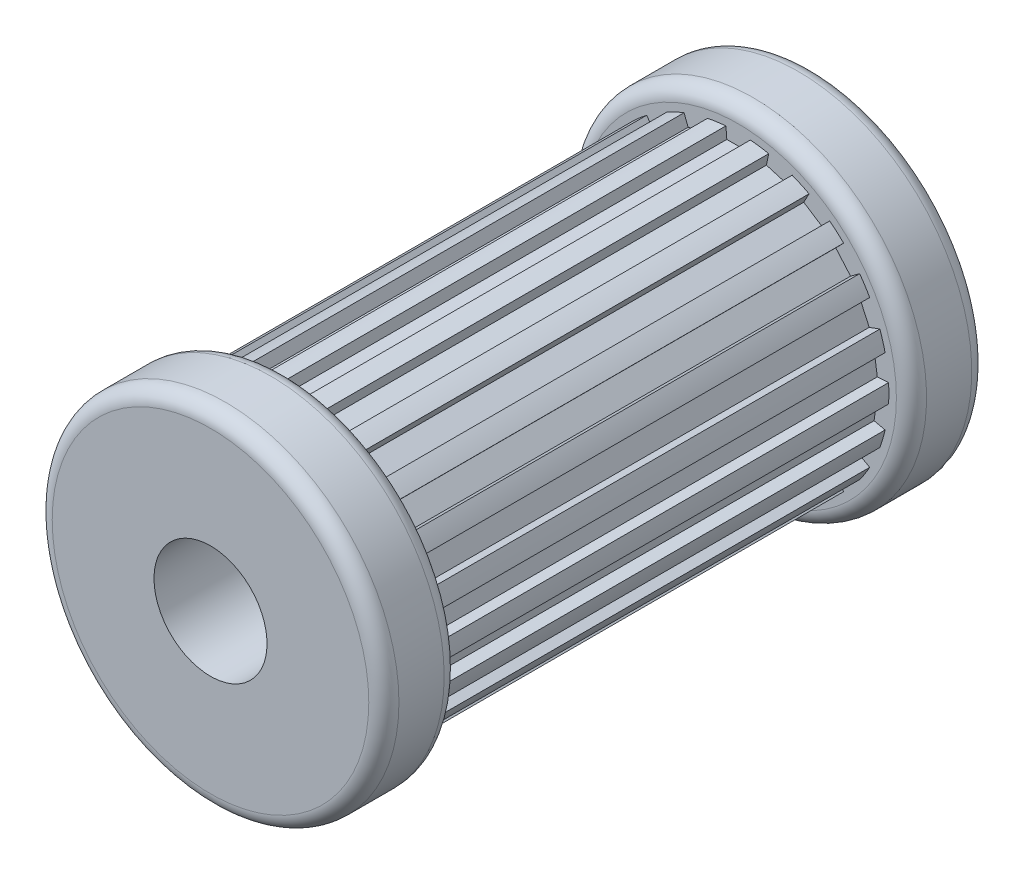
SolidWorks part; units mm, degrees
material "Teak"
ref_plane "Plano frontal" through (0, 0, 0) normal (0, 0, 1) x (1, 0, 0)
ref_plane "Plano superior" through (0, 0, 0) normal (0, 1, 0) x (1, 0, 0)
ref_plane "Plano direito" through (0, 0, 0) normal (1, 0, 0) x (0, 0, -1)
sketch "Sketch1" plane through (0, 0, 0) normal (0, 0, 1) x (1, 0, 0)
  circle A0 centre (0, 0) radius 20
  dimension "D1" = 40
extrude "Boss-Extrude1" add sketch "Sketch1" along normal blind 70
sketch "Sketch2" plane through (0, 0, 70) normal (0, 0, 1) x (1, 0, 0)
  line L1 (-1.5, 18.4391) -> (1.5, 18.4391)
  line L2 (1.5, 18.4391) -> (1.6216, 19.9342)
  line L3 (-1.5, 18.4391) -> (-1.6216, 19.9342)
  circle A0 centre (0, 0) radius 20 construction
  arc A1 (1.6216, 19.9342) -> (-1.6216, 19.9342) centre (0, 0) ccw
  point P6 (0, 18.4391)
  dimension "D1" = 1.5
  dimension "D2" = 3
extrude "Cut-Extrude1" cut sketch "Sketch2" against normal through all
pattern_circular "CirPattern1" count 22 over 360 about axis through (0, 0, 0) along (0, 0, 1) of "Cut-Extrude1"
sketch "Sketch3" plane through (0, 0, 70) normal (0, 0, 1) x (1, 0, 0)
  circle A0 centre (0, 0) radius 23
  dimension "D1" = 46
extrude "Boss-Extrude2" add sketch "Sketch3" against normal blind 10
sketch "Sketch4" plane through (0, 0, 0) normal (0, 0, -1) x (-1, 0, 0)
  circle A0 centre (0, 0) radius 23 construction
  circle A1 centre (0, 0) radius 23
extrude "Boss-Extrude3" add sketch "Sketch4" along normal blind 10
sketch "Sketch5" plane through (0, 0, -10) normal (0, 0, -1) x (-1, 0, 0)
  circle A0 centre (0, 0) radius 7.5
  dimension "D1" = 15
extrude "Cut-Extrude2" cut sketch "Sketch5" against normal through all
fillet "Fillet1" radius 2 4 edges at (23, 0, 60) (23, 0, 70) (-23, 0, 0) (-23, 0, -10)
